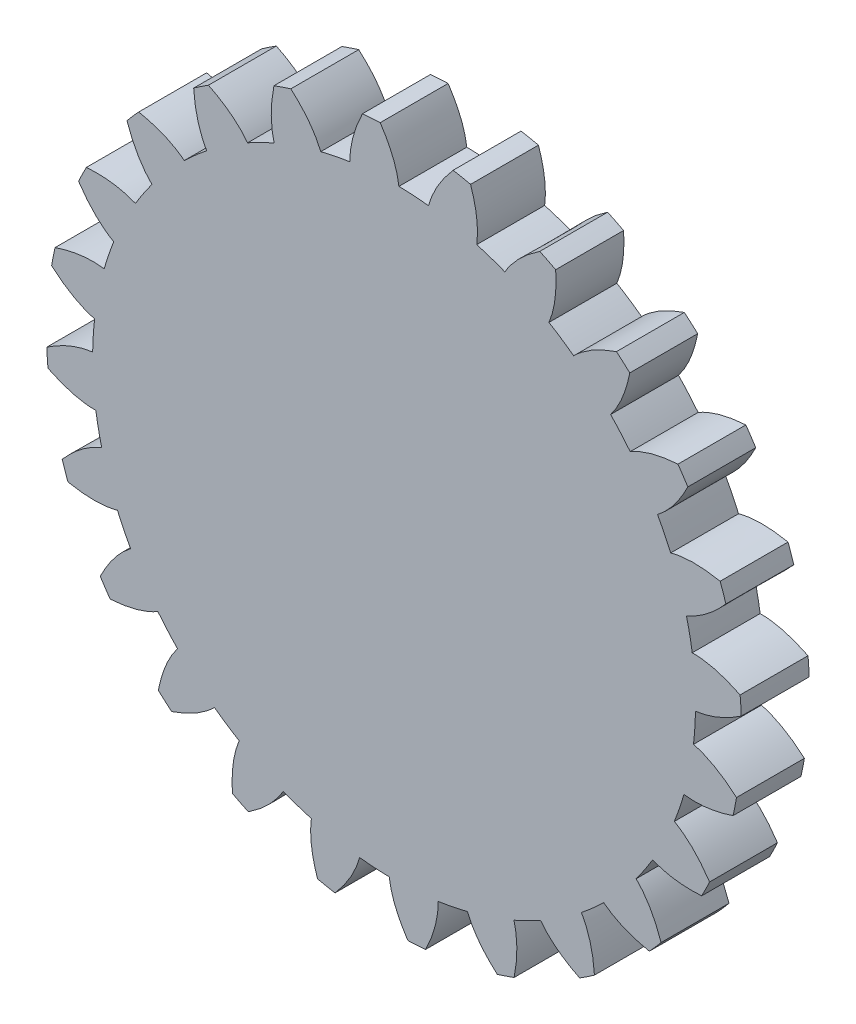
SolidWorks part; units mm, degrees
ref_plane "Front Plane" through (0, 0, 0) normal (0, 0, 1) x (1, 0, 0)
ref_plane "Top Plane" through (0, 0, 0) normal (0, 1, 0) x (1, 0, 0)
ref_plane "Right Plane" through (0, 0, 0) normal (1, 0, 0) x (0, 0, -1)
sketch "Sketch1" plane through (0, 0, 0) normal (0, 0, 1) x (1, 0, 0)
  line L0 (0, -8.3486) -> (0, 32.3486) construction
  line L1 (14.0382, 12) -> (-14.0382, 12) construction
  line L2 (-22.6863, 3.7429) -> (22.6863, 20.2571) construction
  line L3 (0, 0) -> (-3.8567, 10.5963) construction
  line L4 (-8.0591, 7.8871) -> (-1.6913, 14.3938) construction
  line L5 (-0.9262, 11.2382) -> (0.1743, 11.3289) construction
  circle A0 centre (0, 0) radius 12 construction
  circle A1 centre (0, 0) radius 11.2763 construction
  arc A2 (-3.8567, 10.5963) -> (-8.0591, 7.8871) centre (0, 0) ccw
  arc A3 (-3.8567, 10.5963) -> (-0.9262, 11.2382) centre (0, 0) cw
  point P6 (0, 12)
  point P9 (0, 12)
  point P12 (0, 12)
  dimension "D1" = 24
  dimension "D2" = 20
  dimension "D3" = 4.1042
  dimension "D4" = 5
  dimension "D5" = 9.1042
  dimension "D6" = 3
  dimension "D7" = 1.1042
sketch "Sketch2" plane through (0, 0, 0) normal (0, 0, 1) x (1, 0, 0)
  line L0 (1.3933, -21.2582) -> (-1.3933, 21.2582) construction
  line L3 (0, -8.3486) -> (0, 32.3486) construction
  circle A2 centre (0, 0) radius 11.2763 construction
  arc A4 (-0.518, 12.9897) -> (-1.1819, 12.9462) centre (0, 0) ccw
  spline S0 degree 3 poles (0.1816, 11.2748) (0.1506, 11.5223) (-0.005, 12.1193) (-0.309, 12.6764) (-0.518, 12.9897) knots 0 0 0 0 0.203295 0.501255 0.501255 0.501255 0.501255
  spline S1 degree 3 poles (-1.6517, 11.1547) (-1.6533, 11.4041) (-1.577, 12.0163) (-1.3482, 12.6083) (-1.1819, 12.9462) knots 0 0 0 0 0.203295 0.501255 0.501255 0.501255 0.501255
  point P17 (0, 0)
  dimension "D2" = 26
  dimension "D1" = 3.75
sketch "Sketch6" plane through (0, 0, 0) normal (0, 0, 1) x (1, 0, 0)
  arc A0 (-0.518, 12.9897) -> (-1.1819, 12.9462) centre (0, 0) ccw construction
  arc A1 (-0.518, 12.9897) -> (-1.1819, 12.9462) centre (0, 0) ccw
  arc A2 (0.1816, 11.2748) -> (-1.6517, 11.1547) centre (0, 0) ccw
  spline S0 degree 3 poles (-1992.7162, 172.2602) (2021.3868, -275.285) (-2012.8869, 386.6148) (1957.299, -394.967) knots -12.17647 -12.17647 -12.17647 -12.17647 13.803017 13.803017 13.803017 13.803017 only from (0.1816, 11.2748) to (-0.518, 12.9897) construction
  spline S1 degree 3 poles (1953.1837, 430.8881) (-1968.1617, -536.7738) (1945.203, 646.0417) (-1889.0005, -647.0668) knots -12.17647 -12.17647 -12.17647 -12.17647 13.803017 13.803017 13.803017 13.803017 only from (-1.6517, 11.1547) to (-1.1819, 12.9462) construction
  spline S2 degree 3 poles (0.1816, 11.2748) (0.1052, 11.885) (-0.1664, 12.4627) (-0.518, 12.9897) knots 0 0 0 0 0.501255 0.501255 0.501255 0.501255
  spline S3 degree 3 poles (-1.6517, 11.1547) (-1.6556, 11.7696) (-1.4617, 12.3778) (-1.1819, 12.9462) knots 0 0 0 0 0.501255 0.501255 0.501255 0.501255
sketch "Sketch7" plane through (0, 0, 0) normal (0, 0, 1) x (1, 0, 0)
  circle A0 centre (0, 0) radius 11.2763
extrude "Boss-Extrude3" add sketch "Sketch7" along normal blind 2.54
extrude "Boss-Extrude4" add sketch "Sketch6" along normal blind 2.54
pattern_circular "CirPattern2" count 24 over 360 about axis through (0, 0, 2.54) along (0, 0, 1) of "Boss-Extrude4"
equation "\"D5@Sketch1\"=\"D3@Sketch1\"+\"D4@Sketch1\""
equation "\"D7@Sketch1\"=\"D3@Sketch1\"-\"D6@Sketch1\""
